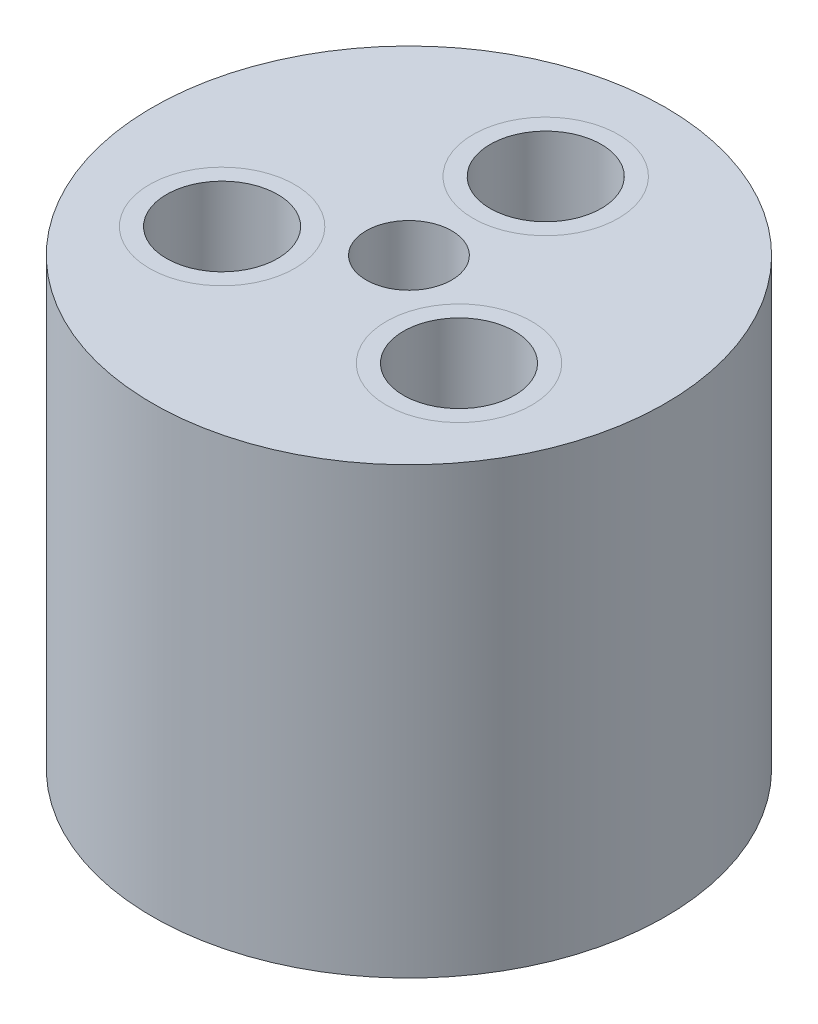
SolidWorks part; units mm, degrees
ref_plane "Ön Düzlem" through (0, 0, 0) normal (0, 0, 1) x (1, 0, 0)
ref_plane "Üst Düzlem" through (0, 0, 0) normal (0, 1, 0) x (1, 0, 0)
ref_plane "Sağ Düzlem" through (0, 0, 0) normal (1, 0, 0) x (0, 0, -1)
sketch "Çizim1" plane through (0, 0, 0) normal (0, 1, 0) x (1, 0, 0)
  circle A0 centre (0, 0) radius 15
  circle A4 centre (0, 0) radius 2.5
  dimension "D1" = 30
  dimension "D2" = 5
extrude "Yükseklik-Ekstrüzyon1" add sketch "Çizim1" along normal blind 26
sketch "Çizim2" plane through (0, 26, 0) normal (0, 1, 0) x (1, 0, 0)
  circle A0 centre (0, 0) radius 8 construction
  circle A1 centre (0, 8) radius 4.25
  circle A4 centre (6.9282, -4) radius 4.25
  circle A6 centre (-6.9282, -4) radius 4.25
  point P5 (3.3077, -11.3226)
  point P18 (0, 0)
  dimension "D1" = 16
  dimension "D2" = 8.5
  dimension "D4" = 3
extrude "Kes-Ekstrüzyon2" cut sketch "Çizim2" against normal through all
sketch "Çizim5" plane through (0, 26, 0) normal (0, 1, 0) x (1, 0, 0)
  line L0 (-4.25, 8) -> (-3.25, 8)
  circle A0 centre (6.9282, -4) radius 4.25 construction
  circle A1 centre (-6.9282, -4) radius 4.25 construction
  circle A2 centre (0, 8) radius 4.25 construction
  circle A3 centre (6.9282, -4) radius 4.25
  circle A4 centre (-6.9282, -4) radius 4.25
  circle A5 centre (0, 8) radius 4.25
  circle A6 centre (0, 8) radius 3.25
  circle A7 centre (-6.9282, -4) radius 3.25
  circle A8 centre (6.9282, -4) radius 3.25
  dimension "D1" = 1
extrude "Yükseklik-Ekstrüzyon4" add sketch "Çizim5" against normal through all separate body
